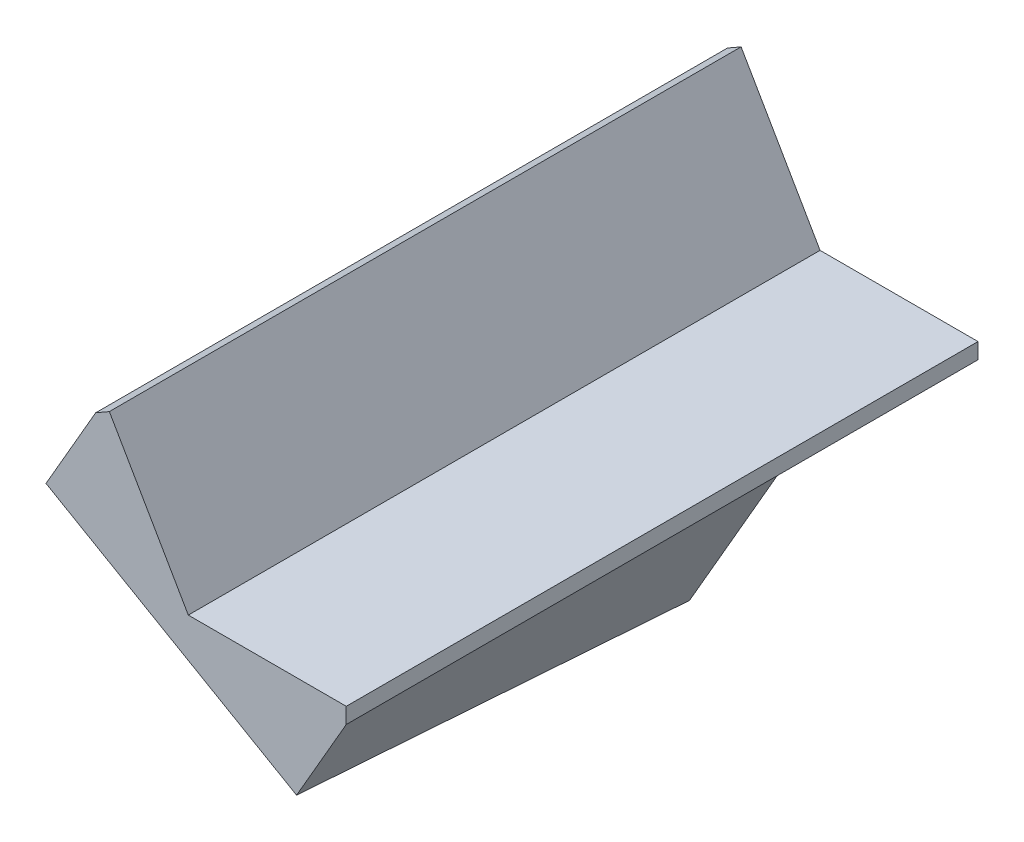
SolidWorks part; units mm, degrees
ref_plane "Front Plane" through (0, 0, 0) normal (0, 0, 1) x (1, 0, 0)
ref_plane "Top Plane" through (0, 0, 0) normal (0, 1, 0) x (1, 0, 0)
ref_plane "Right Plane" through (0, 0, 0) normal (1, 0, 0) x (0, 0, -1)
sketch "Sketch3" plane through (0, 0, 0) normal (0, 0, 1) x (1, 0, 0)
  line L0 (0, 0) -> (-10.5774, 18.3205)
  line L1 (-10.5774, 18.3205) -> (-8.8453, 19.3205)
  line L2 (-8.8453, 19.3205) -> (1.1547, 2)
  line L4 (0, 0) -> (21.1547, 0)
  line L5 (21.1547, 0) -> (21.1547, 2)
  line L6 (21.1547, 2) -> (1.1547, 2)
  dimension "D1" = 2
  dimension "D2" = 20
  dimension "D3" = 120
extrude "Boss-Extrude2" add sketch "Sketch3" along normal blind 80
ref_plane "Plane1" through (0, 0, 0) normal (0.866, -0.5, 0) x (0, 0, -1)
sketch "Sketch5" plane through (0, 0, 0) normal (0.866, -0.5, 0) x (0, 0, -1)
  line L0 (-80, 0) -> (-25.4328, -9.6217) construction
  line L1 (-25.4328, -9.6217) -> (-25.4328, -11.6217)
  line L2 (-25.4328, -11.6217) -> (-80, -2)
  line L3 (-80, -2) -> (-80, 0)
  line L4 (-25.4328, -9.6217) -> (-25.4328, 0)
  line L5 (-80, 0) -> (0, 0) construction
  line L7 (-80, 0) -> (-80, 1)
  line L8 (-80, 0) -> (-80, 10.5774) construction
  line L9 (-80, 1) -> (-25.4328, 1)
  line L10 (-25.4328, 1) -> (-25.4328, 0)
  dimension "D1" = 170
  dimension "D2" = 2
  dimension "D3" = 1
extrude "Boss-Extrude3" add sketch "Sketch5" along normal up to vertex (18.3205 mm away) and the other way up to vertex (18.3205 mm away)
sketch "Sketch6" plane through (0.5, 0.866, 0) normal (0.5, 0.866, 0) x (0, 0, -1)
  line L12 (-25.4328, 18.3205) -> (-80, 18.3205)
  line L13 (-80, 18.3205) -> (-80, 1.7321)
  line L14 (-80, 1.7321) -> (-25.4328, 1.7321)
  line L15 (-80, 1.7321) -> (-25.4328, 1.7321)
  line L16 (-25.4328, 18.3205) -> (-80, 18.3205)
  line L17 (-80, 18.3205) -> (-80, 1.7321)
  line L20 (-25.4328, 1.7321) -> (-25.4328, 18.3205)
  line L21 (-25.4328, 1.7321) -> (-25.4328, 18.3205)
  dimension "D1" = 0
extrude "Boss-Extrude4" add sketch "Sketch6" along normal up to next
sketch "Sketch8" plane through (0.5, 0.866, 0) normal (0.5, 0.866, 0) x (0.866, -0.5, 0)
  line L4 (18.3205, -25.4328) -> (1.7321, -25.4328)
  line L5 (1.7321, -25.4328) -> (1.7321, -80)
  line L6 (1.7321, -80) -> (18.3205, -80)
  line L7 (18.3205, -80) -> (18.3205, -25.4328)
  line L8 (18.3205, -25.4328) -> (1.7321, -25.4328)
  line L9 (1.7321, -25.4328) -> (1.7321, -80)
  line L10 (1.7321, -80) -> (18.3205, -80)
  line L11 (18.3205, -80) -> (18.3205, -25.4328)
  dimension "D1" = 0
extrude "Boss-Extrude5" add sketch "Sketch8" along normal up to next
